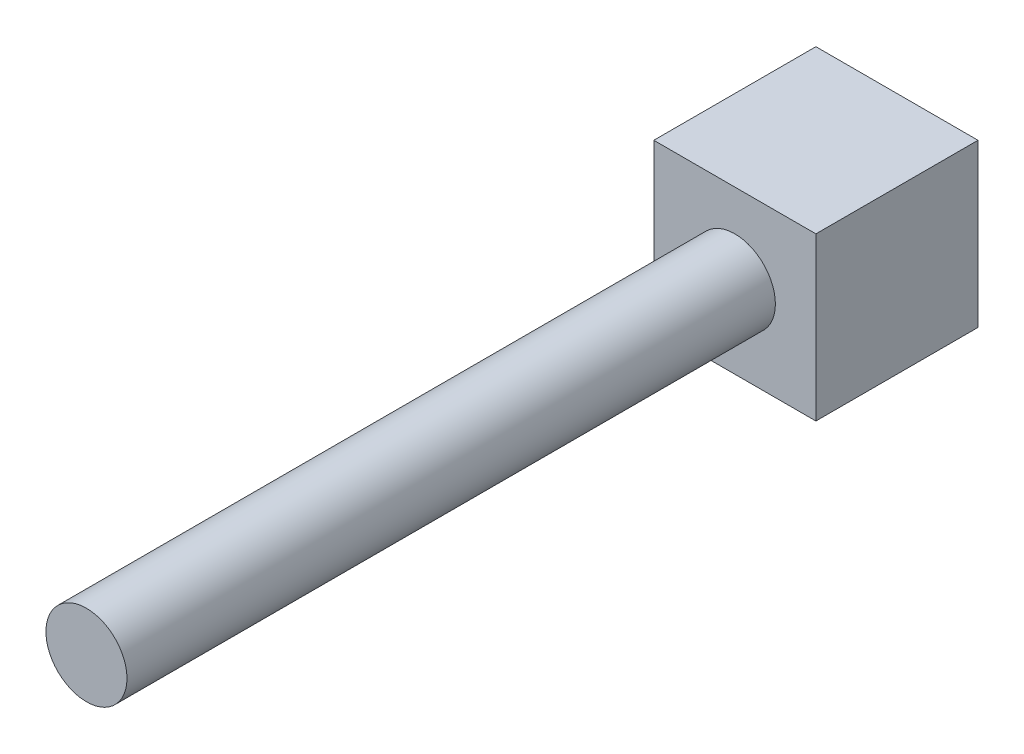
SolidWorks part; units mm, degrees
ref_plane "前视基准面" through (0, 0, 0) normal (0, 0, 1) x (1, 0, 0)
ref_plane "上视基准面" through (0, 0, 0) normal (0, 1, 0) x (1, 0, 0)
ref_plane "右视基准面" through (0, 0, 0) normal (1, 0, 0) x (0, 0, -1)
sketch "草图1" plane through (0, 0, 0) normal (0, 0, 1) x (1, 0, 0)
  line L7 (-5, -5) -> (5, -5)
  line L8 (-5, -5) -> (-5, 5)
  line L9 (-5, 5) -> (5, 5)
  line L10 (5, -5) -> (5, 5)
  line L11 (-5, -5) -> (5, 5) construction
  line L12 (-5, 5) -> (5, -5) construction
  point P0 (0, 0)
  dimension "D1" = 10
  dimension "D2" = 10
extrude "凸台-拉伸1" add sketch "草图1" along normal blind 10
sketch "草图2" plane through (0, 0, 10) normal (0, 0, 1) x (1, 0, 0)
  circle A0 centre (0, 0) radius 2.5
  dimension "D1" = 5
extrude "凸台-拉伸2" add sketch "草图2" along normal blind 40
